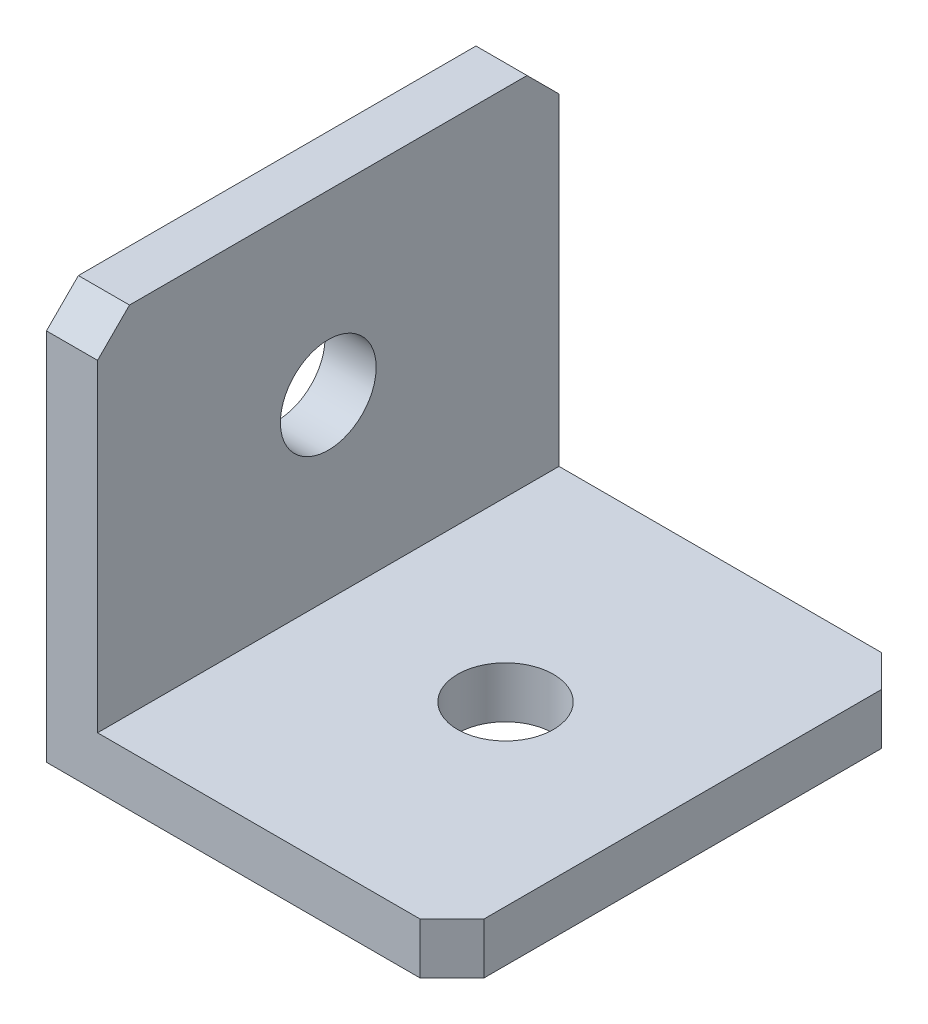
SolidWorks part; units mm, degrees
ref_plane "Plano frontal" through (0, 0, 0) normal (0, 0, 1) x (1, 0, 0)
ref_plane "Plano superior" through (0, 0, 0) normal (0, 1, 0) x (1, 0, 0)
ref_plane "Plano direito" through (0, 0, 0) normal (1, 0, 0) x (0, 0, -1)
sketch "Esboço1" plane through (0, 0, 0) normal (0, 0, 1) x (1, 0, 0)
  line L0 (0, 0) -> (0, 22.2)
  line L1 (0, 22.2) -> (-3.2, 22.2)
  line L2 (-3.2, 22.2) -> (-3.2, -3.2)
  line L3 (-3.2, -3.2) -> (22.2, -3.2)
  line L4 (22.2, -3.2) -> (22.2, 0)
  line L5 (22.2, 0) -> (0, 0)
  dimension "D1" = 3.2
  dimension "D2" = 3.2
  dimension "D3" = 25.4
  dimension "D4" = 25.4
extrude "Ressalto-extrusão1" add sketch "Esboço1" along normal blind 28.9
chamfer "Chanfro1" distance 2 angle 45 4 edges at (-1.6, 22.2, 0) (-1.6, 22.2, 28.9) (22.2, -1.6, 0) (22.2, -1.6, 28.9)
sketch "Esboço2" plane through (0, 0, 0) normal (0, 1, 0) x (1, 0, 0)
  line L0 (11.1, 0) -> (11.1, -28.9) construction
  line L1 (20.2, 0) -> (0, 0) construction
  line L2 (20.2, -28.9) -> (0, -28.9) construction
  line L3 (11.1, -14.45) -> (22.2, -14.45) construction
  line L4 (22.2, -26.9) -> (22.2, -2) construction
  line L5 (11.1, -14.45) -> (0, -14.45) construction
  line L6 (0, -28.9) -> (0, 0) construction
  circle A0 centre (11.1, -14.45) radius 3
  dimension "D1" = 6
extrude "Corte-extrusão1" cut sketch "Esboço2" against normal through all
sketch "Esboço3" plane through (0, 0, 0) normal (1, 0, 0) x (0, 0, -1)
  line L0 (-28.9, 11.1) -> (0, 11.1) construction
  line L1 (-28.9, 0) -> (-28.9, 20.2) construction
  line L2 (0, 0) -> (0, 20.2) construction
  line L3 (-14.45, 11.1) -> (-14.45, 22.2) construction
  line L4 (-26.9, 22.2) -> (-2, 22.2) construction
  line L5 (-14.45, 0) -> (-14.45, 11.1) construction
  line L6 (-28.9, 0) -> (0, 0) construction
  circle A0 centre (-14.45, 11.1) radius 3
  dimension "D1" = 6
extrude "Corte-extrusão2" cut sketch "Esboço3" against normal through all
